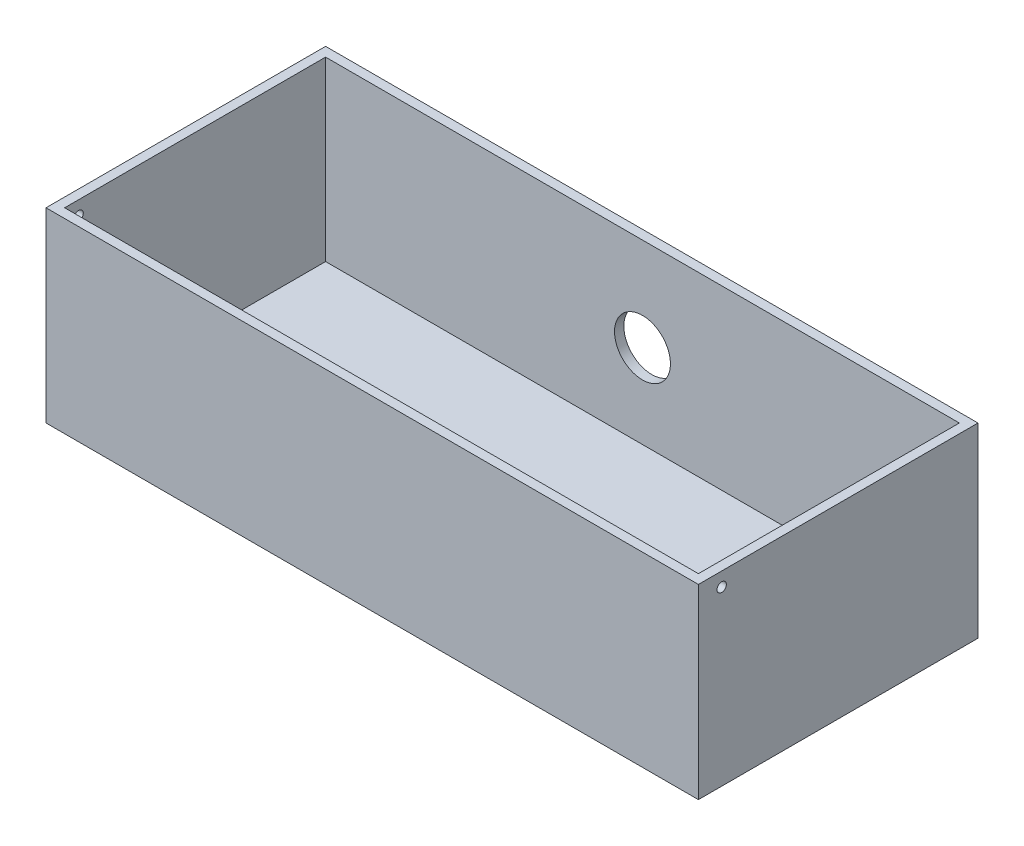
SolidWorks part; units mm, degrees
ref_plane "Alzado" through (0, 0, 0) normal (0, 0, 1) x (1, 0, 0)
ref_plane "Planta" through (0, 0, 0) normal (0, 1, 0) x (1, 0, 0)
ref_plane "Vista lateral" through (0, 0, 0) normal (1, 0, 0) x (0, 0, -1)
sketch "Croquis1" plane through (0, 0, 0) normal (0, 1, 0) x (1, 0, 0)
  line L1 (-350, -150) -> (350, -150)
  line L2 (-350, -150) -> (-350, 150)
  line L3 (-350, 150) -> (350, 150)
  line L4 (350, -150) -> (350, 150)
  line L5 (-350, -150) -> (350, 150) construction
  line L6 (-350, 150) -> (350, -150) construction
  point P1 (0, 0)
  dimension "D1" = 700
  dimension "D2" = 300
extrude "Saliente-Extruir1" add sketch "Croquis1" along normal blind 200
sketch "Croquis2" plane through (0, 200, 0) normal (0, 1, 0) x (1, 0, 0)
  line L1 (-340, -140) -> (340, -140)
  line L2 (-340, -140) -> (-340, 140)
  line L3 (-340, 140) -> (340, 140)
  line L4 (340, -140) -> (340, 140)
  line L5 (-340, -140) -> (340, 140) construction
  line L6 (-340, 140) -> (340, -140) construction
  point P0 (0, 0)
  dimension "D1" = 680
  dimension "D2" = 280
extrude "Cortar-Extruir1" cut sketch "Croquis2" against normal blind 190
sketch "Croquis3" plane through (350, 0, 0) normal (1, 0, 0) x (0, 0, -1)
  line L0 (-150, 200) -> (150, 200) construction
  line L1 (-150, 200) -> (-150, 0) construction
  circle A0 centre (-125, 185) radius 5
  dimension "D1" = 15
  dimension "D2" = 25
extrude "Cortar-Extruir2" cut sketch "Croquis3" against normal blind 700
sketch "Croquis4" plane through (0, 0, -150) normal (0, 0, -1) x (-1, 0, 0)
  line L0 (-350, 200) -> (350, 200) construction
  line L1 (-350, 200) -> (-350, 0) construction
  circle A0 centre (0, 100) radius 30
  point P4 (-350, 100)
  dimension "D1" = 100
  dimension "D2" = 350
extrude "Cortar-Extruir3" cut sketch "Croquis4" against normal up to surface (10 mm away) up to face at (0, 105, -140)
